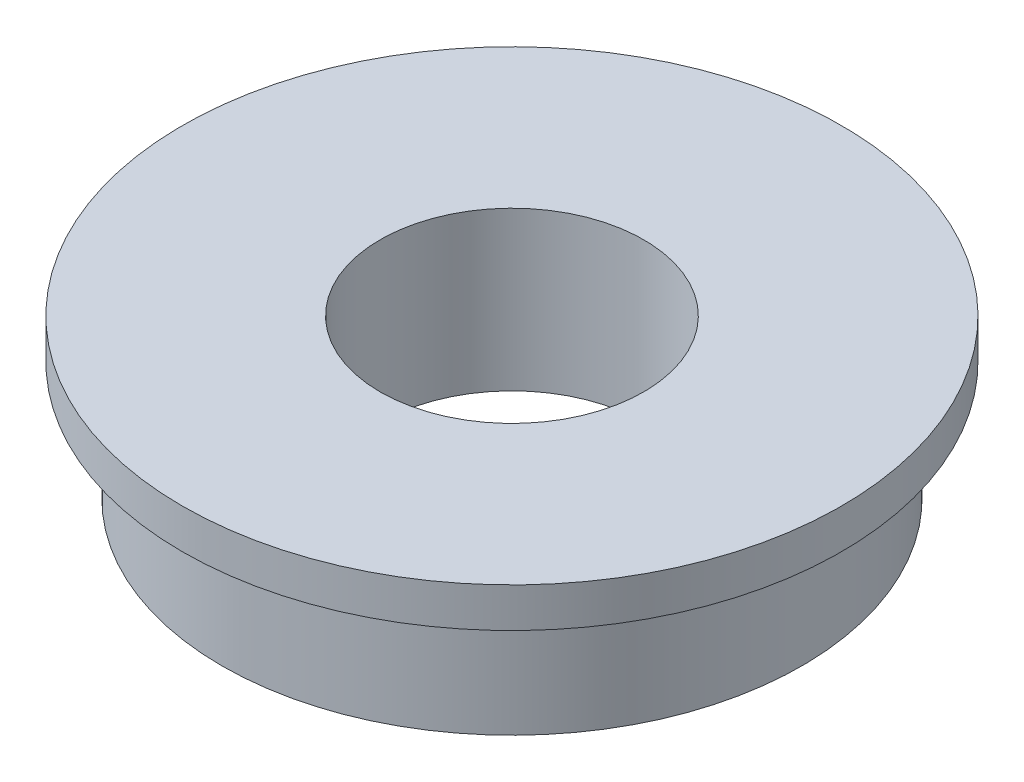
SolidWorks part; units mm, degrees
ref_plane "前视基准面" through (0, 0, 0) normal (0, 0, 1) x (1, 0, 0)
ref_plane "上视基准面" through (0, 0, 0) normal (0, 1, 0) x (1, 0, 0)
ref_plane "右视基准面" through (0, 0, 0) normal (1, 0, 0) x (0, 0, -1)
sketch "Sketch1" plane through (0, 0, 0) normal (0, 1, 0) x (1, 0, 0)
  circle A0 centre (0, 0) radius 5
  circle A1 centre (0, 0) radius 11
extrude "Boss-Extrude1" add sketch "Sketch1" along normal blind 4.5
sketch "Sketch2" plane through (0, 4.5, 0) normal (0, 1, 0) x (1, 0, 0)
  circle A0 centre (0, 0) radius 12.5
  circle A1 centre (0, 0) radius 5
extrude "Boss-Extrude2" add sketch "Sketch2" along normal blind 1.5
